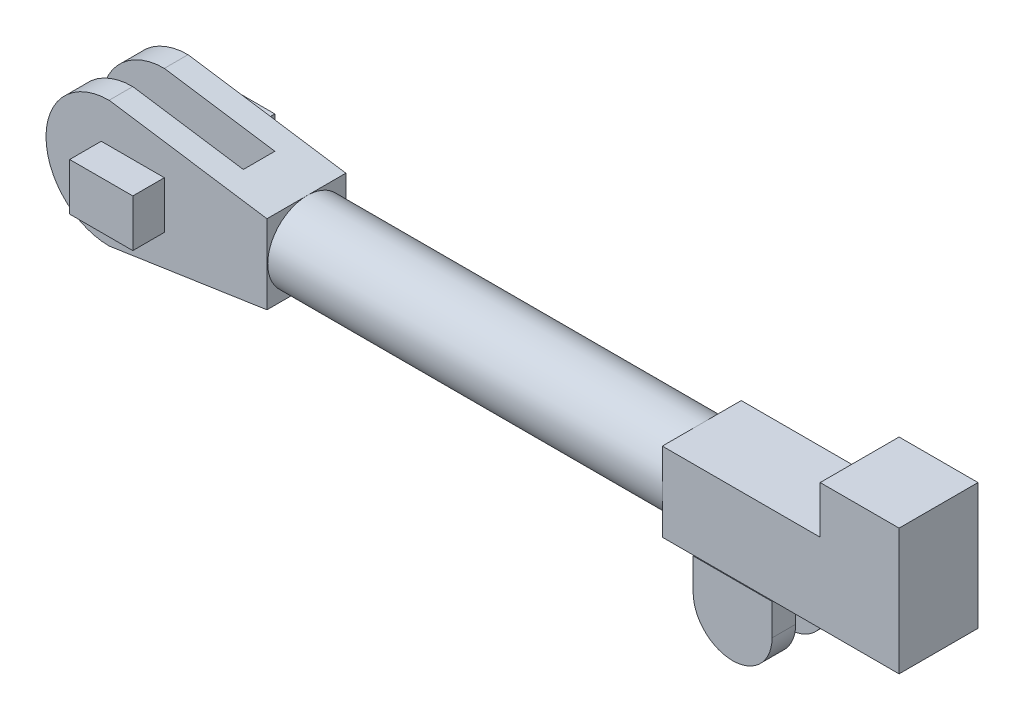
SolidWorks part; units mm, degrees
ref_plane "Front Plane" through (0, 0, 0) normal (0, 0, 1) x (1, 0, 0)
ref_plane "Top Plane" through (0, 0, 0) normal (0, 1, 0) x (1, 0, 0)
ref_plane "Right Plane" through (0, 0, 0) normal (1, 0, 0) x (0, 0, -1)
sketch "Sketch9" plane through (0, 0, 0) normal (0, 0, 1) x (1, 0, 0)
  line L0 (0, 101.6) -> (254, 63.5)
  line L1 (0, 0) -> (124.7182, 0) construction
  line L2 (254, 63.5) -> (254, 0)
  line L3 (254, -63.5) -> (254, 0)
  line L4 (0, -101.6) -> (254, -63.5)
  arc A0 (0, 101.6) -> (0, -101.6) centre (0, 0) ccw
  dimension "D1" = 101.6
  dimension "D2" = 63.5
  dimension "D3" = 254
extrude "Boss-Extrude2" add sketch "Sketch9" along normal blind 127
ref_plane "Plane1" through (0, 101.6, 0) normal (0, 1, 0) x (1, 0, 0)
sketch "Sketch11" plane through (0, 101.6, 0) normal (0, 1, 0) x (1, 0, 0)
  line L0 (254, -127) -> (0, -127) construction
  line L1 (254, -127) -> (254, 0) construction
  line L3 (177.8, -88.9) -> (-101.6, -88.9)
  line L4 (177.8, -88.9) -> (177.8, -38.1)
  line L5 (177.8, -38.1) -> (-101.6, -38.1)
  line L6 (-101.6, -88.9) -> (-101.6, -38.1)
  line L7 (177.8, -88.9) -> (-101.6, -38.1) construction
  line L8 (177.8, -38.1) -> (-101.6, -88.9) construction
  point P0 (38.1, -63.5)
  point P5 (38.1, -63.5)
  dimension "D1" = 63.5
  dimension "D2" = 215.9
  dimension "D3" = 279.4
  dimension "D4" = 50.8
extrude "Cut-Extrude1" cut sketch "Sketch11" against normal through all
sketch "Sketch12" plane through (254, 0, 0) normal (1, 0, 0) x (0, 0, -1)
  line L0 (-127, 63.5) -> (0, 63.5) construction
  circle A0 centre (-62.2801, 0) radius 63.5
  dimension "D1" = 127
extrude "Boss-Extrude3" add sketch "Sketch12" along normal blind 635
sketch "Sketch13" plane through (0, 0, 127) normal (0, 0, 1) x (1, 0, 0)
  line L0 (254, -63.5) -> (254, 63.5) construction
  line L1 (-12.7, 38.1) -> (88.9, 38.1)
  line L2 (-12.7, 38.1) -> (-12.7, -38.1)
  line L3 (-12.7, -38.1) -> (88.9, -38.1)
  line L4 (88.9, 38.1) -> (88.9, -38.1)
  line L5 (-12.7, 38.1) -> (88.9, -38.1) construction
  line L6 (-12.7, -38.1) -> (88.9, 38.1) construction
  point P0 (38.1, 0)
  dimension "D1" = 215.9
  dimension "D2" = 101.6
  dimension "D3" = 76.2
extrude "Boss-Extrude4" add sketch "Sketch13" along normal blind 50.8
ref_plane "Plane2" through (0, 0, 63.5) normal (0, 0, 1) x (1, 0, 0)
mirror "Mirror1" about plane through (0, 0, 63.5) normal (0, 0, 1) of "Boss-Extrude4"
sketch "Sketch14" plane through (889, 0, 0) normal (1, 0, 0) x (0, 0, -1)
  line L1 (-125.7801, 63.5) -> (1.2199, 63.5)
  line L2 (-125.7801, 63.5) -> (-125.7801, -63.5)
  line L3 (-125.7801, -63.5) -> (1.2199, -63.5)
  line L4 (1.2199, 63.5) -> (1.2199, -63.5)
  line L5 (-125.7801, 63.5) -> (1.2199, -63.5) construction
  line L6 (-125.7801, -63.5) -> (1.2199, 63.5) construction
  point P0 (-62.2801, 0)
  dimension "D1" = 127
  dimension "D2" = 127
extrude "Boss-Extrude6" add sketch "Sketch14" along normal blind 254
sketch "Sketch15" plane through (1143, 0, 0) normal (1, 0, 0) x (0, 0, -1)
  line L1 (-125.7801, -63.5) -> (1.2199, -63.5)
  line L2 (-125.7801, -63.5) -> (-125.7801, 139.7)
  line L3 (-125.7801, 139.7) -> (1.2199, 139.7)
  line L4 (1.2199, -63.5) -> (1.2199, 139.7)
  dimension "D1" = 203.2
  dimension "D2" = 127
extrude "Boss-Extrude7" add sketch "Sketch15" along normal blind 127
sketch "Sketch16" plane through (0, 0, 63.5) normal (0, 0, 1) x (1, 0, 0)
  line L0 (939.8, -63.5) -> (939.8, -114.3)
  line L1 (1270, -63.5) -> (889, -63.5) construction
  line L2 (939.8, -114.3) -> (1066.8, -114.3)
  line L3 (1066.8, -114.3) -> (1066.8, -63.5)
  line L4 (889, 0) -> (889, -63.5) construction
  line L12 (889, 63.5) -> (889, 0)
  line L13 (889, 0) -> (889, -63.5)
  line L14 (889, -63.5) -> (1270, -63.5)
  line L15 (1270, -63.5) -> (1270, 139.7)
  line L16 (1270, 139.7) -> (1143, 139.7)
  line L17 (1143, 139.7) -> (1143, 63.5)
  line L18 (1143, 63.5) -> (889, 63.5)
  line L21 (939.8, -63.5) -> (1066.8, -63.5)
  dimension "D1" = 50.8
  dimension "D2" = 127
  dimension "D3" = 50.8
  dimension "D4" = 0
extrude "Boss-Extrude9" add sketch "Sketch16" along normal blind 63.5
sketch "Sketch20" plane through (0, 0, 127) normal (0, 0, 1) x (1, 0, 0)
  line L0 (939.8, -114.3) -> (1066.8, -114.3)
  arc A0 (939.8, -114.3) -> (1066.8, -114.3) centre (1003.3, -114.3) ccw
extrude "Boss-Extrude10" add sketch "Sketch20" against normal blind 38.1
mirror "Mirror2" about plane through (0, 0, 63.5) normal (0, 0, 1) of "Boss-Extrude10", "Boss-Extrude9"
sketch "Sketch21" plane through (0, 0, 38.1) normal (0, 0, 1) x (1, 0, 0)
  circle A0 centre (0, 0) radius 12.7
  dimension "D1" = 25.4
extrude "Boss-Extrude11" add sketch "Sketch21" along normal blind 50.8
sketch "Sketch22" plane through (0, 0, 38.1) normal (0, 0, 1) x (1, 0, 0)
  line L0 (1066.8, -114.3) -> (939.8, -114.3) construction
  circle A0 centre (1003.3, -139.7) radius 12.7
  dimension "D2" = 25.4
  dimension "D1" = 25.4
extrude "Boss-Extrude12" add sketch "Sketch22" along normal blind 50.8
sketch "Sketch24" plane through (1066.8, 0, 0) normal (1, 0, 0) x (0, 0, -1)
  line L0 (0, -63.5) -> (-125.7801, -63.5) construction
  line L1 (-38.1, -114.3) -> (-89.0226, -114.3)
  line L2 (-38.1, -114.3) -> (-38.1, -63.5)
  line L3 (-38.1, -63.5) -> (-89.0226, -63.5)
  line L4 (-89.0226, -114.3) -> (-89.0226, -63.5)
  dimension "D1" = 50.8
extrude "Cut-Extrude2" cut sketch "Sketch24" against normal blind 271.018
